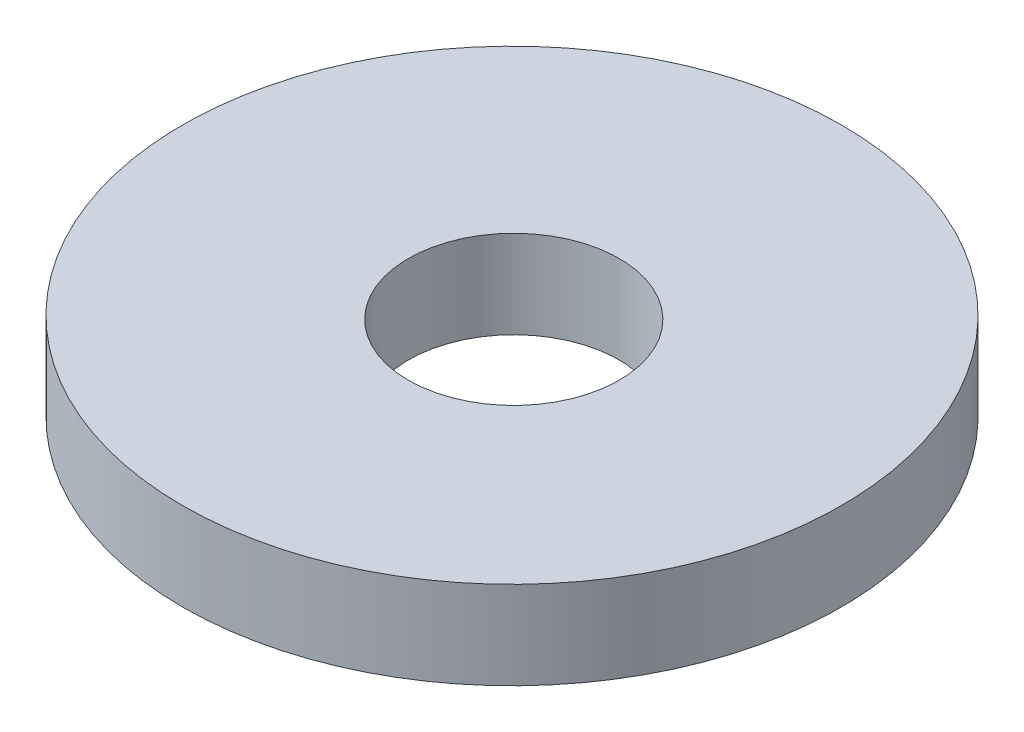
SolidWorks part; units mm, degrees
ref_plane "Front Plane" through (0, 0, 0) normal (0, 0, 1) x (1, 0, 0)
ref_plane "Top Plane" through (0, 0, 0) normal (0, 1, 0) x (1, 0, 0)
ref_plane "Right Plane" through (0, 0, 0) normal (1, 0, 0) x (0, 0, -1)
sketch "Sketch1" plane through (0, 0, 0) normal (0, 1, 0) x (1, 0, 0)
  circle A0 centre (0, 0) radius 3.75
  dimension "D1" = 7.5
extrude "Boss-Extrude1" add sketch "Sketch1" along normal blind 1
hole_wizard "M2 Clearance Hole1" positions "Sketch3" profile "Sketch2" hole size "M2" standard "ANSI Metric" end condition through all
sketch "Sketch3" plane through (0, 1, 0) normal (0, 1, 0) x (1, 0, 0)
  point P0 (0.0504, -0.0302)
sketch "Sketch2" plane through (0.0504, 1, 0.0302) normal (1, 0, 0) x (0, 0, 1)
  line L0 (0, 0) -> (0, 1)
  line L1 (0, 1) -> (1.2, 1)
  line L2 (1.2, 1) -> (1.2, 0)
  line L5 (1.2, 0) -> (0, 0)
  line L11 (0, -6.35) -> (0, 107.95) construction
  dimension "Thru Hole Dia." = 2.4
  dimension "Thru Hole Depth" = 1
